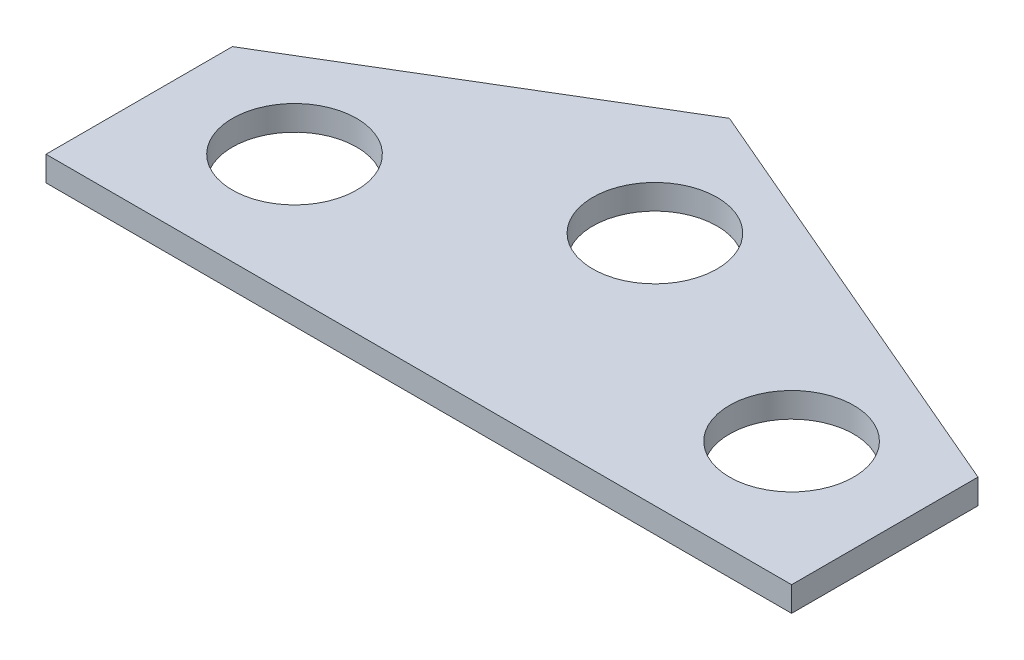
SolidWorks part; units mm, degrees
ref_plane "Front Plane" through (0, 0, 0) normal (0, 0, 1) x (1, 0, 0)
ref_plane "Top Plane" through (0, 0, 0) normal (0, 1, 0) x (1, 0, 0)
ref_plane "Right Plane" through (0, 0, 0) normal (1, 0, 0) x (0, 0, -1)
sketch "Sketch1" plane through (0, 0, 0) normal (0, 1, 0) x (1, 0, 0)
  line L1 (0, 0) -> (60, 0)
  line L2 (0, 0) -> (0, 30)
  line L3 (0, 30) -> (60, 30)
  line L4 (60, 0) -> (60, 30)
  dimension "D1" = 60
  dimension "D2" = 30
extrude "Boss-Extrude1" add sketch "Sketch1" along normal blind 2
sketch "Sketch2" plane through (0, 2, 0) normal (0, 1, 0) x (1, 0, 0)
  line L0 (60, 30) -> (0, 30) construction
  line L1 (0, 30) -> (0, 0) construction
  line L2 (0, 0) -> (60, 0) construction
  line L3 (60, 0) -> (60, 30) construction
  line L4 (0, 15) -> (25, 30)
  line L5 (25, 30) -> (60, 15)
  line L6 (60, 15) -> (60, 30)
  line L7 (60, 30) -> (25, 30)
  line L8 (0, 30) -> (0, 15)
  point P0 (25, 30)
  point P5 (0, 15)
  point P8 (60, 15)
  point P12 (60, 15)
  dimension "D1" = 25
  dimension "D2" = 15
  dimension "D3" = 15
extrude "Cut-Extrude1" cut sketch "Sketch2" against normal through all contours L0 L4 L3 | L3 L5 L2
sketch "Sketch3" plane through (0, 0, 0) normal (0, -1, 0) x (1, 0, 0)
  line L0 (0, 0) -> (60, 0) construction
  line L1 (0, -15) -> (0, 0) construction
  line L2 (30, 0) -> (30, -33) construction
  line L3 (0, -15) -> (25, -30) construction
  circle A0 centre (10, -10) radius 5
  circle A1 centre (50, -10) radius 5
  circle A2 centre (30, -19) radius 5
  dimension "D3" = 10
  dimension "D1" = 10
  dimension "D2" = 10
  dimension "D4" = 19
  dimension "D5" = 30
extrude "Cut-Extrude2" cut sketch "Sketch3" against normal through all
